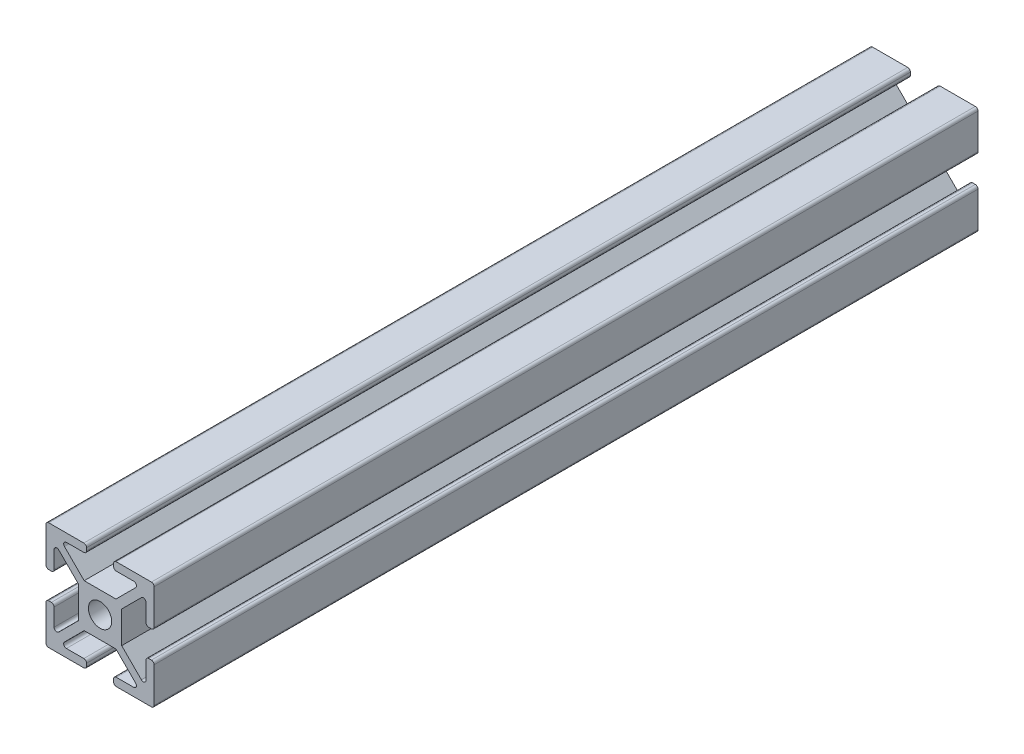
SolidWorks part; units mm, degrees
material "6061 Alloy"
ref_plane "Front Plane" through (0, 0, 0) normal (0, 0, 1) x (1, 0, 0)
ref_plane "Top Plane" through (0, 0, 0) normal (0, 1, 0) x (1, 0, 0)
ref_plane "Right Plane" through (0, 0, 0) normal (1, 0, 0) x (0, 0, -1)
sketch "Sketch1" plane through (0, 0, 0) normal (0, 0, 1) x (1, 0, 0)
  line L0 (-10, 2.5) -> (-8.5, 2.5)
  line L1 (-2.9393, 4) -> (0, 4)
  line L2 (-2.5, 10) -> (-10, 10)
  line L3 (-7.4393, 8.5) -> (-2.9393, 4)
  line L4 (-2.5, 8.5) -> (-7.4393, 8.5)
  line L5 (-8.5, 2.5) -> (-8.5, 7.4393)
  line L6 (-8.5, 7.4393) -> (-4, 2.9393)
  line L7 (-4, 2.9393) -> (-4, 0)
  line L8 (-4, 0) -> (-10, 0) construction
  line L9 (0, 10) -> (0, -10) construction
  line L10 (-10, 10) -> (0, 0) construction
  line L11 (-10, 2.5) -> (-10, 10)
  line L12 (-2.5, 10) -> (-2.5, 8.5)
  line L13 (-2.5, 10) -> (0, 10) construction
  line L14 (-10, 2.5) -> (-10, 0) construction
  line L15 (2.9393, 4) -> (0, 4)
  line L16 (4, 2.9393) -> (4, 0)
  line L17 (8.5, 7.4393) -> (4, 2.9393)
  line L18 (8.5, 2.5) -> (8.5, 7.4393)
  line L19 (10, 2.5) -> (8.5, 2.5)
  line L20 (10, 2.5) -> (10, 10)
  line L21 (2.5, 10) -> (10, 10)
  line L22 (2.5, 10) -> (2.5, 8.5)
  line L23 (2.5, 8.5) -> (7.4393, 8.5)
  line L24 (7.4393, 8.5) -> (2.9393, 4)
  line L25 (4, -2.9393) -> (4, 0)
  line L26 (2.9393, -4) -> (0, -4)
  line L27 (7.4393, -8.5) -> (2.9393, -4)
  line L28 (2.5, -8.5) -> (7.4393, -8.5)
  line L29 (2.5, -10) -> (2.5, -8.5)
  line L30 (2.5, -10) -> (10, -10)
  line L31 (10, -2.5) -> (10, -10)
  line L32 (10, -2.5) -> (8.5, -2.5)
  line L33 (8.5, -2.5) -> (8.5, -7.4393)
  line L34 (8.5, -7.4393) -> (4, -2.9393)
  line L35 (-2.9393, -4) -> (0, -4)
  line L36 (-4, -2.9393) -> (-4, 0)
  line L37 (-8.5, -7.4393) -> (-4, -2.9393)
  line L38 (-8.5, -2.5) -> (-8.5, -7.4393)
  line L39 (-10, -2.5) -> (-8.5, -2.5)
  line L40 (-10, -2.5) -> (-10, -10)
  line L41 (-2.5, -10) -> (-10, -10)
  line L42 (-2.5, -10) -> (-2.5, -8.5)
  line L43 (-2.5, -8.5) -> (-7.4393, -8.5)
  line L44 (-7.4393, -8.5) -> (-2.9393, -4)
  circle A0 centre (0, 0) radius 2.15
  point P53 (0, 0)
  dimension "D2" = 4.3
  dimension "D1" = 10
  dimension "D3" = 2.5
  dimension "D4" = 1.5
  dimension "D5" = 1.5
  dimension "D6" = 4
  dimension "D7" = 4
extrude "Boss-Extrude1" add sketch "Sketch1" along normal blind 152.4
fillet "Fillet1" radius 0.5 28 edges at (8.5, 2.5, 76.2) (2.5, 8.5, 76.2) (2.5, 10, 76.2) (2.5, -10, 76.2) (-10, 2.5, 76.2) (-8.5, -7.4393, 76.2) (-10, -10, 76.2) (-8.5, 7.4393, 76.2) (-7.4393, 8.5, 76.2) (7.4393, 8.5, 76.2) (8.5, -7.4393, 76.2) (7.4393, -8.5, 76.2) (-7.4393, -8.5, 76.2) (2.5, -8.5, 76.2) (-2.5, -10, 76.2) (-2.5, -8.5, 76.2) (10, -10, 76.2) (8.5, -2.5, 76.2) (10, -2.5, 76.2) (10, 2.5, 76.2) (-10, -2.5, 76.2) (-8.5, -2.5, 76.2) (-8.5, 2.5, 76.2) (-2.5, 8.5, 76.2) (-2.5, 10, 76.2) (-10, 10, 76.2) (10, 10, 76.2) (8.5, 7.4393, 76.2)
